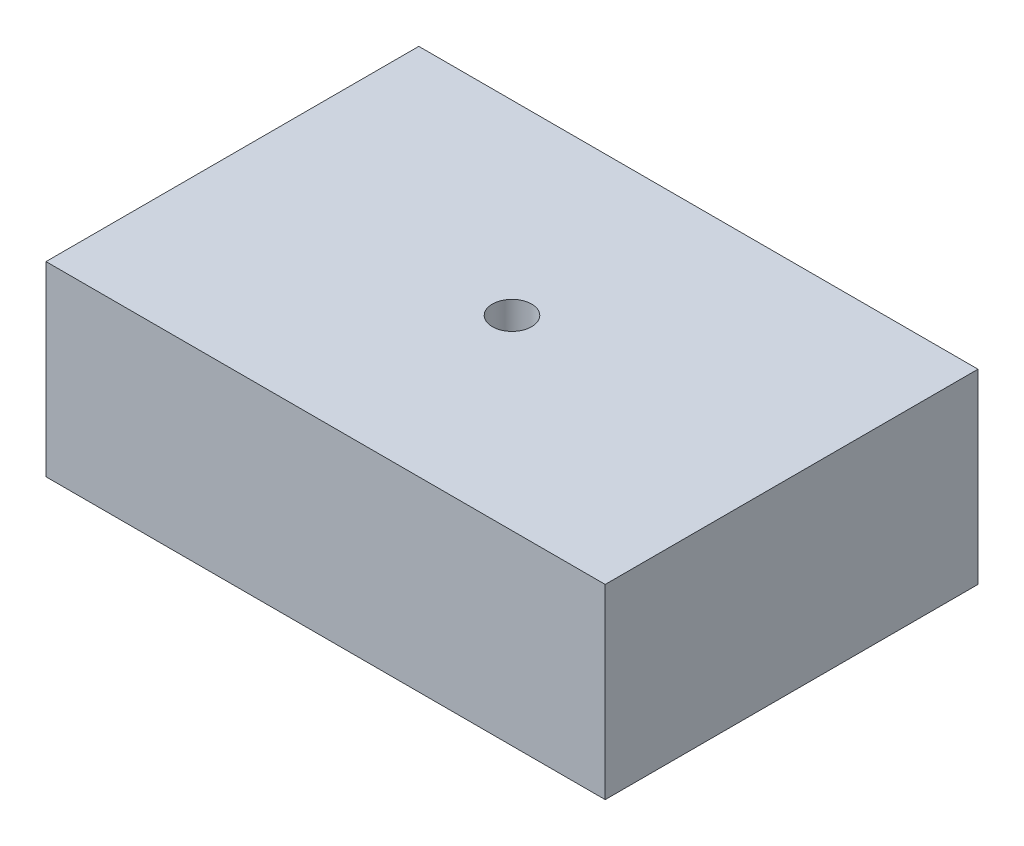
SolidWorks part; units mm, degrees
ref_plane "Front Plane" through (0, 0, 0) normal (0, 0, 1) x (1, 0, 0)
ref_plane "Top Plane" through (0, 0, 0) normal (0, 1, 0) x (1, 0, 0)
ref_plane "Right Plane" through (0, 0, 0) normal (1, 0, 0) x (0, 0, -1)
sketch "Sketch1" plane through (0, 0, 0) normal (0, 1, 0) x (1, 0, 0)
  line L1 (-15, 10) -> (15, 10)
  line L2 (-15, 10) -> (-15, -10)
  line L3 (-15, -10) -> (15, -10)
  line L4 (15, 10) -> (15, -10)
  line L5 (-15, 10) -> (15, -10) construction
  line L6 (-15, -10) -> (15, 10) construction
  circle A0 centre (0, 0) radius 1.055
  point P0 (0, 0)
extrude "Boss-Extrude1" add sketch "Sketch1" along normal blind 10
